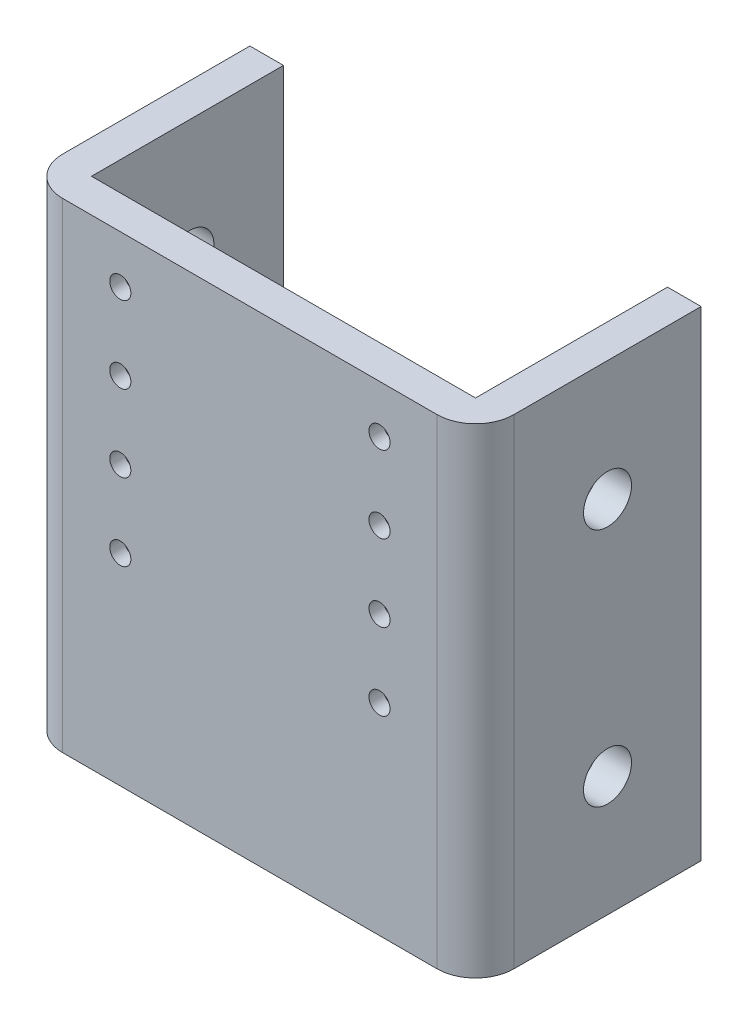
SolidWorks part; units mm, degrees
ref_plane "Alzado" through (0, 0, 0) normal (0, 0, 1) x (1, 0, 0)
ref_plane "Planta" through (0, 0, 0) normal (0, 1, 0) x (1, 0, 0)
ref_plane "Vista lateral" through (0, 0, 0) normal (1, 0, 0) x (0, 0, -1)
sketch "Croquis1" plane through (0, 0, 0) normal (0, 0, 1) x (1, 0, 0)
  line L1 (-18, -25) -> (18, -25)
  line L2 (-18, -25) -> (-18, 25)
  line L3 (-18, 25) -> (18, 25)
  line L4 (18, -25) -> (18, 25)
  line L5 (-18, -25) -> (18, 25) construction
  line L6 (-18, 25) -> (18, -25) construction
  point P0 (0, 0)
  dimension "D1" = 36
  dimension "D2" = 50
extrude "Saliente-Extruir1" add sketch "Croquis1" along normal blind 3.5
sketch "Croquis2" plane through (0, 0, 3.5) normal (0, 0, 1) x (1, 0, 0)
  line L0 (0, 0) -> (0, 20) construction
  line L1 (0, 20) -> (-13.5, 20) construction
  circle A0 centre (-13.5, 20) radius 1.1
  circle A1 centre (13.5, 20) radius 1.1
  circle A2 centre (13.5, 12) radius 1.1
  circle A3 centre (13.5, 4) radius 1.1
  circle A4 centre (13.5, -4) radius 1.1
  circle A5 centre (-13.5, 12) radius 1.1
  circle A6 centre (-13.5, 4) radius 1.1
  circle A7 centre (-13.5, -4) radius 1.1
  dimension "D1" = 2.2
  dimension "D4" = 13.5
  dimension "D5" = 20
  dimension "D2" = 2
  dimension "D3" = 4
extrude "Cortar-Extruir2" cut sketch "Croquis2" against normal blind 5
sketch "Croquis5" plane through (0, 25, 0) normal (0, 1, 0) x (1, 0, 0)
  line L0 (0, 0) -> (-20, 0) construction
  line L1 (0, 0) -> (0, 5) construction
  line L2 (-20, 0) -> (-23.5, 0)
  line L3 (-20, 0) -> (-20, 20)
  line L4 (-20, 20) -> (-23.5, 20)
  line L5 (-23.5, 0) -> (-23.5, 20)
  line L6 (-23.5, 0) -> (-18, 0)
  line L7 (-23.5, 0) -> (-23.5, -3.5)
  line L8 (-23.5, -3.5) -> (-18, -3.5)
  line L9 (-18, 0) -> (-18, -3.5)
  line L10 (23.5, -3.5) -> (18, -3.5)
  line L11 (18, 0) -> (18, -3.5)
  line L12 (23.5, 0) -> (18, 0)
  line L13 (23.5, 0) -> (23.5, -3.5)
  line L14 (20, 20) -> (23.5, 20)
  line L15 (23.5, 0) -> (23.5, 20)
  line L16 (20, 0) -> (23.5, 0)
  line L17 (20, 0) -> (20, 20)
  line M11 (-18, 0) -> (-18, -3.5)
  line M13 (18, -3.5) -> (18, 0)
  dimension "D1" = 3.5
  dimension "D2" = 20
  dimension "D3" = 20
extrude "Saliente-Extruir3" add sketch "Croquis5" against normal through all contours L7 L8 L6 L2 M11 | L5 L2 L3 L4 | L13 L12 L10 M13 | L17 L12 L15 L14
fillet "Redondeo1" radius 4 2 edges at (-23.5, 0, 3.5) (23.5, 0, 3.5)
sketch "Croquis6" plane through (0, 0, 0) normal (0, 0, -1) x (-1, 0, 0)
  circle A0 centre (-13.5, 20) radius 2.25
  circle A1 centre (13.5, 20) radius 2.25
  circle A2 centre (13.5, 12) radius 2.25
  circle A3 centre (13.5, 4) radius 2.25
  circle A4 centre (13.5, -4) radius 2.25
  circle A5 centre (-13.5, 12) radius 2.25
  circle A6 centre (-13.5, 4) radius 2.25
  circle A7 centre (-13.5, -4) radius 2.25
  dimension "D1" = 2
  dimension "D2" = 4
extrude "Cortar-Extruir3" cut sketch "Croquis6" against normal blind 2
sketch "Croquis8" plane through (23.5, 0, 0) normal (1, 0, 0) x (0, 0, -1)
  line L0 (10.25, 25) -> (10.25, 12.5) construction
  line L1 (20, 25) -> (0.5, 25) construction
  line L2 (0, 0) -> (20, 0) construction
  line L3 (20, -25) -> (20, 25) construction
  circle A0 centre (10.25, 12.5) radius 2.5
  circle A1 centre (10.25, -12.5) radius 2.5
extrude "Cortar-Extruir4" cut sketch "Croquis8" against normal through all
